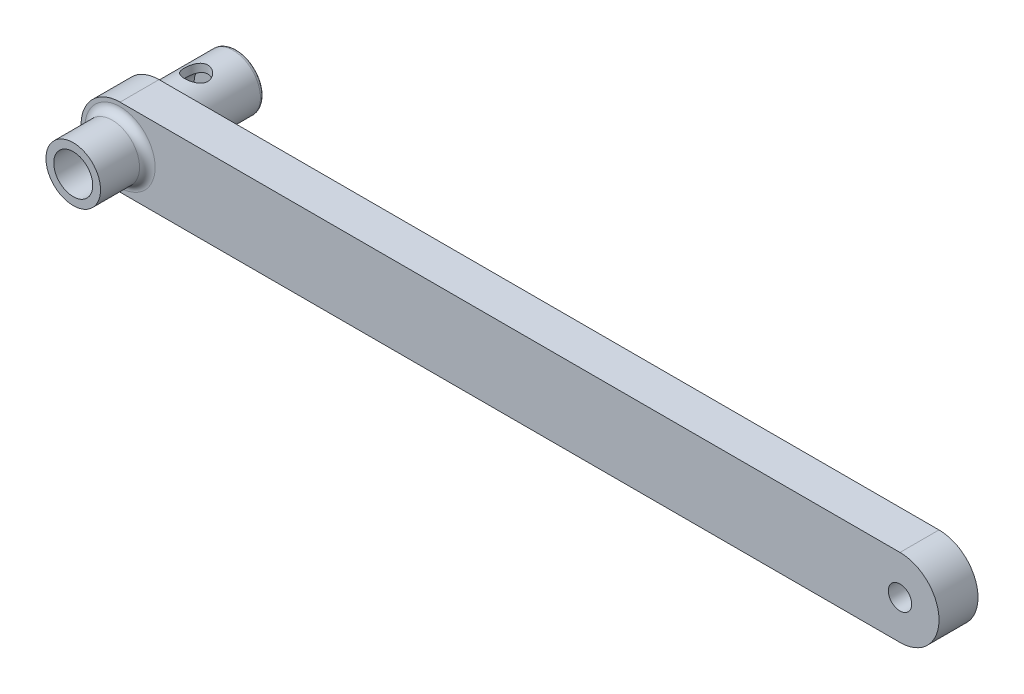
SolidWorks part; units mm, degrees
ref_plane "Plan de face" through (0, 0, 0) normal (0, 0, 1) x (1, 0, 0)
ref_plane "Plan de dessus" through (0, 0, 0) normal (0, 1, 0) x (1, 0, 0)
ref_plane "Plan de droite" through (0, 0, 0) normal (1, 0, 0) x (0, 0, -1)
sketch "Esquisse1" plane through (0, 0, 0) normal (0, 0, 1) x (1, 0, 0)
  line L0 (-50, 0) -> (50, 0) construction
  line L1 (-50, 5) -> (50, 5)
  line L2 (-50, -5) -> (50, -5)
  arc A0 (-50, 5) -> (-50, -5) centre (-50, 0) ccw
  arc A1 (50, -5) -> (50, 5) centre (50, 0) ccw
  circle A2 centre (-50, 0) radius 2.5
  circle A3 centre (50, 0) radius 1.5
  point P2 (0, 0)
  dimension "D2" = 5
  dimension "D3" = 5
  dimension "D4" = 3
  dimension "D1" = 100
extrude "Boss.-Extru.1" add sketch "Esquisse1" along normal blind 5
sketch "Esquisse2" plane through (0, 0, 5) normal (0, 0, 1) x (1, 0, 0)
  circle A0 centre (-50, 0) radius 2.5 construction
  circle A1 centre (-50, 0) radius 2.5
  circle A2 centre (-50, 0) radius 3.5
  dimension "D1" = 7
extrude "Boss.-Extru.2" add sketch "Esquisse2" against normal blind 10 from offset 5 offset against normal yes
sketch "Esquisse3" plane through (0, 0, -10) normal (0, 0, -1) x (-1, 0, 0)
  circle A0 centre (50, 0) radius 3.5
extrude "Boss.-Extru.3" add sketch "Esquisse3" against normal blind 3
fillet "Congé1" radius 0.5 1 edges at (-46.5, 0, -10)
sketch "Esquisse4" plane through (0, 0, 0) normal (0, 1, 0) x (1, 0, 0)
  line L0 (-50, 9.5) -> (-50, 0) construction
  line L1 (-46.5, 9.5) -> (-53.5, 9.5) construction
  circle A0 centre (-50, 4.75) radius 1.5
  dimension "D1" = 3
extrude "Enlèv. mat.-Extru.1" cut sketch "Esquisse4" against normal through all and the other way through all
sketch "Esquisse5" plane through (0, 0, 5) normal (0, 0, 1) x (1, 0, 0)
  circle A0 centre (-50, 0) radius 2.5 construction
  circle A1 centre (-50, 0) radius 2.5
  circle A2 centre (-50, 0) radius 3.5
  dimension "D1" = 7
extrude "Boss.-Extru.4" add sketch "Esquisse5" along normal blind 6
fillet "Congé2" radius 1 1 edges at (-46.5, 0, 5)
fillet "Congé3" radius 1 1 edges at (-46.5, 0, 0)
